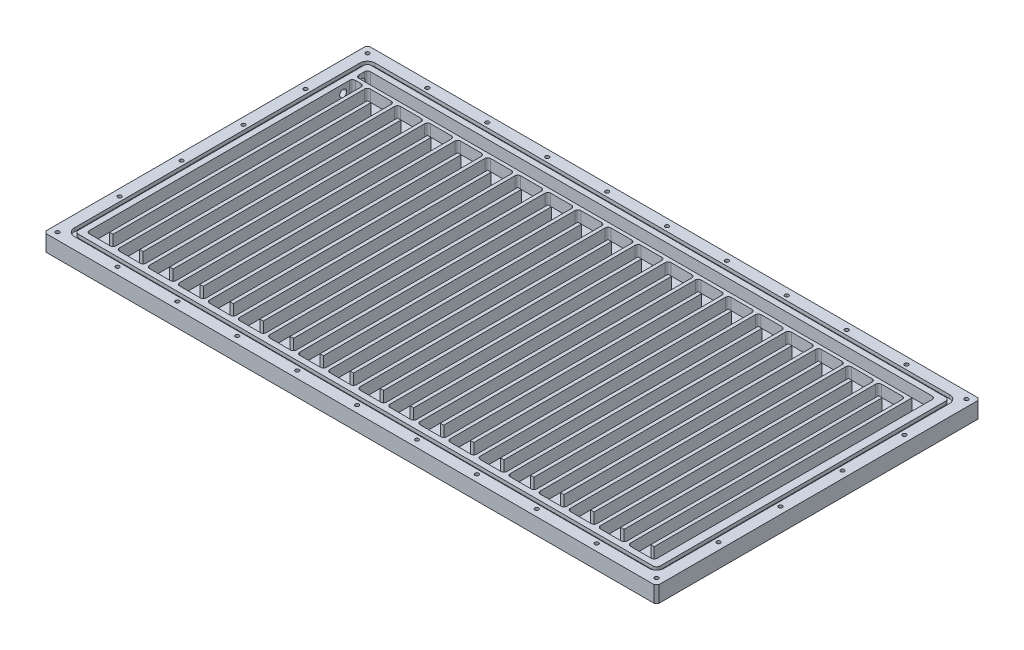
SolidWorks part; units mm, degrees
material "6063-T6"
ref_plane "Front Plane" through (0, 0, 0) normal (0, 0, 1) x (1, 0, 0)
ref_plane "Top Plane" through (0, 0, 0) normal (0, 1, 0) x (1, 0, 0)
ref_plane "Right Plane" through (0, 0, 0) normal (1, 0, 0) x (0, 0, -1)
sketch "Sketch1" plane through (0, 0, 0) normal (0, 1, 0) x (1, 0, 0)
  line L0 (265, 0) -> (265, 140)
  line L1 (0, 0) -> (265, 0)
  line L2 (0, 0) -> (0, 140)
  line L3 (0, 140) -> (265, 140)
  line L5 (213.2, 6) -> (265, 6) construction
  circle A0 centre (6, 113.2) radius 1.65 construction
  circle A1 centre (6, 59.6) radius 1.65 construction
  circle A2 centre (6, 6) radius 1.65 construction
  circle A3 centre (57.8, 6) radius 1.65 construction
  circle A4 centre (109.6, 6) radius 1.65 construction
  circle A5 centre (161.4, 6) radius 1.65 construction
  circle A6 centre (213.2, 6) radius 1.65 construction
  point P20 (265, 6)
  dimension "D3" = 3.3
  dimension "D4" = 3.3
  dimension "D5" = 3.3
  dimension "D6" = 3.3
  dimension "D7" = 3.3
  dimension "D8" = 3.3
  dimension "D9" = 3.3
  dimension "D1" = 265
  dimension "D2" = 140
  dimension "D10" = 6
  dimension "D11" = 6
  dimension "D12" = 6
  dimension "D13" = 6
  dimension "D14" = 6
  dimension "D15" = 6
  dimension "D16" = 6
  dimension "D17" = 6
  dimension "D20" = 51.8
  dimension "D21" = 51.8
  dimension "D22" = 51.8
  dimension "D23" = 51.8
  dimension "D24" = 53.6
  dimension "D25" = 53.6
  dimension "D18" = 51.8
extrude "Boss-Extrude1" add sketch "Sketch1" along normal blind 14
sketch "Sketch2" plane through (0, 14, 0) normal (0, 1, 0) x (1, 0, 0)
  line L0 (265, 140) -> (0, 140) construction
  line L1 (10, 140) -> (13.5, 140)
  line L2 (10, 140) -> (10, 10)
  line L3 (10, 10) -> (14.8949, 10)
  line L4 (13.5, 140) -> (13.5, 13.5)
  line L5 (265, 0) -> (265, 140) construction
  line L6 (14.8949, 10) -> (265, 10)
  line L8 (13.5, 13.5) -> (265, 13.5)
  line L9 (265, 10) -> (265, 13.5)
  line L10 (0, 140) -> (0, 0) construction
  line L11 (0, 0) -> (265, 0) construction
  dimension "D1" = 10
  dimension "D2" = 10
  dimension "D3" = 3.5
  dimension "D4" = 3.5
extrude "Cut-Extrude1" cut sketch "Sketch2" against normal blind 3
fillet "Fillet1" radius 3 1 edges at (13.5, 12.5, -13.5)
fillet "Fillet2" radius 6.5 1 edges at (10, 12.5, -10)
mirror "Mirror1" about plane through (265, 14, 0) normal (-1, 0, 0) of bodies 102
mirror "Mirror2" about plane through (0, 14, -140) normal (0, 0, 1) of bodies 103
hole_wizard "M4x0.7 Tapped Hole1" positions "3DSketch6" profile "Sketch13" tap size "M4x0.7" standard "BSI" end condition through all
sketch3d "3DSketch6"
  point P22 (6, 0, -113.2)
  point P24 (6, 0, -59.6)
  point P26 (6, 0, -6)
  point P28 (57.8, 0, -6)
  point P30 (109.6, 0, -6)
  point P32 (161.4, 0, -6)
  point P34 (213.2, 0, -6)
  point P36 (265, 0, -6)
cosmetic thread "Hole Thread2" parameters "D2"=4
cosmetic thread "Hole Thread3" parameters "D2"=4
cosmetic thread "Hole Thread4" parameters "D2"=4
cosmetic thread "Hole Thread5" parameters "D2"=4
cosmetic thread "Hole Thread6" parameters "D2"=4
cosmetic thread "Hole Thread7" parameters "D2"=4
cosmetic thread "Hole Thread8" parameters "D2"=4
cosmetic thread "Hole Thread9" parameters "D2"=4
sketch "Sketch13" plane through (6, 0, -113.2) normal (1, 0, 0) x (0, 0, -1)
  line L0 (0, 0) -> (0, 14)
  line L1 (0, 14) -> (1.65, 14)
  line L2 (1.65, 14) -> (1.65, 0)
  line L5 (1.65, 0) -> (0, 0)
  line L11 (0, -6.35) -> (0, 107.95) construction
  dimension "Thru Tap Drill Dia." = 3.3
  dimension "Thru Tap Drill Depth" = 14
ref_plane "Plane35" through (0, 0, -140) normal (0, 0, 1) x (1, 0, 0)
ref_plane "Plane36" through (265, 0, 0) normal (1, 0, 0) x (0, 0, -1)
mirror "Mirror3" about plane through (0, 0, -140) normal (0, 0, 1) of "M4x0.7 Tapped Hole1"
mirror "Mirror4" about plane through (265, 0, 0) normal (1, 0, 0) of "Mirror3", "M4x0.7 Tapped Hole1"
sketch "Sketch3" plane through (0, 14, 0) normal (0, 1, 0) x (1, 0, 0)
  line L1 (18.5, 18.5) -> (28.5, 18.5)
  line L2 (18.5, 18.5) -> (18.5, 248.5)
  line L3 (18.5, 248.5) -> (28.5, 248.5)
  line L4 (28.5, 18.5) -> (28.5, 248.5)
  line L5 (13.5, 16.5) -> (13.5, 263.5) construction
  line L6 (513.5, 266.5) -> (16.5, 266.5) construction
  line L7 (513.5, 13.5) -> (16.5, 13.5) construction
  dimension "D1" = 10
  dimension "D2" = 5
  dimension "D3" = 18
  dimension "D4" = 5
extrude "Cut-Extrude2" cut sketch "Sketch3" against normal blind 10
pattern_linear "LPattern1" count 38 spacing 13 along (1, 0, 0) of "Cut-Extrude2"
sketch "Sketch4" plane through (0, 14, 0) normal (0, 1, 0) x (1, 0, 0)
  line L0 (31.5, 248.5) -> (31.5, 18.5) construction
  line L1 (28.5, 18.5) -> (31.5, 18.5)
  line L2 (28.5, 18.5) -> (28.5, 28.5)
  line L3 (28.5, 28.5) -> (31.5, 28.5)
  line L4 (31.5, 18.5) -> (31.5, 28.5)
  dimension "D1" = 10
extrude "Cut-Extrude3" cut sketch "Sketch4" against normal blind 10
pattern_linear "LPattern2" count 19 spacing 26 along (1, 0, 0) of "Cut-Extrude3"
sketch "Sketch5" plane through (0, 14, 0) normal (0, 1, 0) x (1, 0, 0)
  line L0 (44.5, 248.5) -> (44.5, 18.5) construction
  line L1 (41.5, 248.5) -> (44.5, 248.5)
  line L2 (41.5, 248.5) -> (41.5, 238.5)
  line L3 (41.5, 238.5) -> (44.5, 238.5)
  line L4 (44.5, 248.5) -> (44.5, 238.5)
  dimension "D1" = 10
extrude "Cut-Extrude4" cut sketch "Sketch5" against normal blind 10
pattern_linear "LPattern3" count 18 spacing 26 along (1, 0, 0) of "Cut-Extrude4"
sketch "Sketch6" plane through (0, 14, 0) normal (0, 1, 0) x (1, 0, 0)
  line L1 (18.5, 261.5) -> (509.5, 261.5)
  line L2 (18.5, 261.5) -> (18.5, 251.5)
  line L3 (18.5, 251.5) -> (499.5, 251.5)
  line L5 (18.5, 248.5) -> (18.5, 18.5) construction
  line L6 (513.5, 266.5) -> (16.5, 266.5) construction
  line L7 (499.5, 251.5) -> (499.5, 248.5)
  line L12 (499.5, 248.5) -> (509.5, 248.5)
  line L13 (509.5, 248.5) -> (509.5, 261.5)
  dimension "D1" = 90
  dimension "D2" = 270
  dimension "D3" = 0
  dimension "D4" = 5
  dimension "D5" = 10
extrude "Cut-Extrude5" cut sketch "Sketch6" against normal blind 10
fillet "Fillet3" radius 2.5 76 edges at (18.5, 9, -18.5) (41.5, 9, -18.5) (44.5, 9, -18.5) (67.5, 9, -18.5) (70.5, 9, -18.5) (93.5, 9, -18.5) (96.5, 9, -18.5) (119.5, 9, -18.5) (122.5, 9, -18.5) (145.5, 9, -18.5) (148.5, 9, -18.5) (171.5, 9, -18.5) (174.5, 9, -18.5) (197.5, 9, -18.5) (200.5, 9, -18.5) (223.5, 9, -18.5) (226.5, 9, -18.5) (249.5, 9, -18.5) (252.5, 9, -18.5) (275.5, 9, -18.5) (278.5, 9, -18.5) (301.5, 9, -18.5) (304.5, 9, -18.5) (327.5, 9, -18.5) (330.5, 9, -18.5) (353.5, 9, -18.5) (356.5, 9, -18.5) (379.5, 9, -18.5) (382.5, 9, -18.5) (405.5, 9, -18.5) (408.5, 9, -18.5) (431.5, 9, -18.5) (434.5, 9, -18.5) (457.5, 9, -18.5) (460.5, 9, -18.5) (483.5, 9, -18.5) (486.5, 9, -18.5) (509.5, 9, -261.5) (509.5, 9, -18.5) (473.5, 9, -248.5) (447.5, 9, -248.5) (421.5, 9, -248.5) (395.5, 9, -248.5) (369.5, 9, -248.5) (343.5, 9, -248.5) (317.5, 9, -248.5) (291.5, 9, -248.5) (265.5, 9, -248.5) (239.5, 9, -248.5) (213.5, 9, -248.5) (187.5, 9, -248.5) (161.5, 9, -248.5) (135.5, 9, -248.5) (109.5, 9, -248.5) (57.5, 9, -248.5) (31.5, 9, -248.5) (496.5, 9, -248.5) (470.5, 9, -248.5) (444.5, 9, -248.5) (418.5, 9, -248.5) (392.5, 9, -248.5) (366.5, 9, -248.5) (340.5, 9, -248.5) (314.5, 9, -248.5) (288.5, 9, -248.5) (262.5, 9, -248.5) (236.5, 9, -248.5) (210.5, 9, -248.5) (83.5, 9, -248.5) (106.5, 9, -248.5) (184.5, 9, -248.5) (158.5, 9, -248.5) (132.5, 9, -248.5) (80.5, 9, -248.5) (54.5, 9, -248.5) (28.5, 9, -248.5)
sketch "Sketch7" plane through (0, 0, 0) normal (-1, 0, 0) x (0, 0, 1)
  line L2 (-280, 14) -> (-280, 0) construction
  line L4 (-280, 14) -> (0, 14) construction
  circle A0 centre (-256.5, 7) radius 4.35
  dimension "D1" = 8.7
  dimension "D2" = 7
  dimension "D3" = 23.5
fillet "Fillet4" radius 2.5 1 edges at (18.5, 9, -248.5)
ref_plane "Plane33" through (265, 0, 0) normal (-1, 0, 0) x (0, 0, 1)
ref_plane "Plane34" through (0, 0, -140) normal (0, 0, 1) x (1, 0, 0)
chamfer "Chamfer1" distance 2 angle 45 4 edges at (0, 7, -280) (530, 7, -280) (530, 7, 0) (0, 7, 0)
hole_wizard "G1/8 Tapped Hole1" positions "3DSketch1" profile "Sketch8" tap size "G1/8" standard "BSI"
sketch3d "3DSketch1"
  point P0 (0, 7, -256.5)
sketch "Sketch8" plane through (0, 7, -256.5) normal (0, 1, 0) x (0, 0, 1)
  line L0 (0, 0) -> (0, 11.3638)
  line L1 (0, 11.3638) -> (4.4, 8.72)
  line L2 (4.4, 8.72) -> (4.4, 0)
  line L5 (4.4, 0) -> (0, 0)
  line L10 (0, 11.3638) -> (-4.4, 8.72) construction
  line L11 (0, -6.35) -> (0, 107.95) construction
  dimension "Tap Drill Dia." = 8.8
  dimension "Tap Drill Depth" = 8.72
  dimension "Drill Angle" = 118
cosmetic thread "Hole Thread1" parameters "D1"=6, "D2"=9.728
fillet "Fillet5" radius 2.5 2 edges at (18.5, 9, -251.5) (18.5, 9, -261.5)
hole_wizard "Ø6.0 (6) Diameter Hole1" positions "3DSketch2" profile "Sketch10" hole size "Ø6.0" standard "BSI"
sketch3d "3DSketch2"
  point P0 (0, 7, -256.5)
sketch "Sketch10" plane through (0, 7, -256.5) normal (0, 1, 0) x (0, 0, 1)
  line L0 (0, 0) -> (0, 23.8026)
  line L1 (0, 23.8026) -> (3, 22)
  line L2 (3, 22) -> (3, 0)
  line L5 (3, 0) -> (0, 0)
  line L10 (0, 23.8026) -> (-3, 22) construction
  line L11 (0, -6.35) -> (0, 107.95) construction
  dimension "Hole Dia." = 6
  dimension "Hole Depth" = 22
  dimension "Drill Angle" = 118
pattern_linear "LPattern10" count 2 spacing 16 along (0, 0, 1) of "G1/8 Tapped Hole1", "Ø6.0 (6) Diameter Hole1"
equation "\"D1@Sketch1\"=530/2"
equation "\"D2@Sketch1\"=280/2"
equation "\"D4@Sketch1\"=\"D3@Sketch1\""
equation "\"D5@Sketch1\"=\"D3@Sketch1\""
equation "\"D6@Sketch1\"=\"D3@Sketch1\""
equation "\"D7@Sketch1\"=\"D3@Sketch1\""
equation "\"D8@Sketch1\"=\"D3@Sketch1\""
equation "\"D9@Sketch1\"=\"D3@Sketch1\""
equation "\"D11@Sketch1\"=\"D10@Sketch1\""
equation "\"D12@Sketch1\"=\"D10@Sketch1\""
equation "\"D14@Sketch1\"=\"D13@Sketch1\""
equation "\"D15@Sketch1\"=\"D13@Sketch1\""
equation "\"D16@Sketch1\"=\"D13@Sketch1\""
equation "\"D17@Sketch1\"=\"D13@Sketch1\""
equation "\"D23@Sketch1\"=\"D22@Sketch1\""
equation "\"D22@Sketch1\"=\"D20@Sketch1\""
equation "\"D21@Sketch1\"=\"D20@Sketch1\""
equation "\"D25@Sketch1\"=\"D24@Sketch1\""
equation "\"D20@Sketch1\"=(530-2*\"D10@Sketch1\")/10"
equation "\"D24@Sketch1\"=(280-2*\"D13@Sketch1\")/5"
equation "\"D18@Sketch1\"=\"D23@Sketch1\""
